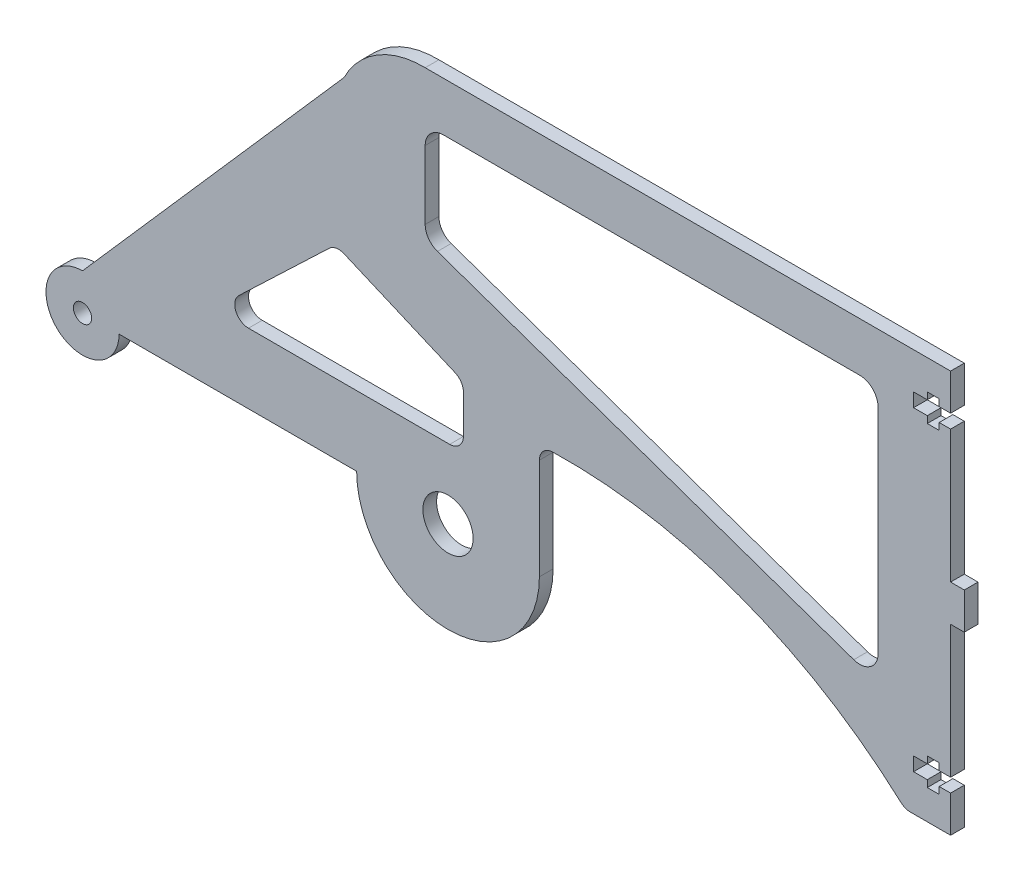
SolidWorks part; units mm, degrees
ref_plane "前视基准面" through (0, 0, 0) normal (0, 0, 1) x (1, 0, 0)
ref_plane "上视基准面" through (0, 0, 0) normal (0, 1, 0) x (1, 0, 0)
ref_plane "右视基准面" through (0, 0, 0) normal (1, 0, 0) x (0, 0, -1)
sketch "草图1" plane through (0, 0, 0) normal (0, 0, 1) x (1, 0, 0)
  line L308 (254.0026, 13.7079) -> (254.0026, 53.7079) construction
  line L334 (234.0026, 13.7079) -> (182.0026, 13.7079)
  line L346 (364.0026, 97.7079) -> (354.0026, 97.7079)
  line L347 (364.0026, 97.7079) -> (364.0026, 89.7079)
  line L348 (361.5026, 89.7079) -> (361.5026, 91.2079)
  line L349 (361.5026, 86.7079) -> (361.5026, 85.2079)
  line L350 (364.0026, 86.7079) -> (361.5026, 86.7079)
  line L351 (361.5026, 91.2079) -> (358.9026, 91.2079)
  line L352 (358.9026, 91.2079) -> (358.9026, 89.7079)
  line L353 (358.9026, 89.7079) -> (355.9026, 89.7079)
  line L354 (355.9026, 86.7079) -> (355.9026, 89.7079)
  line L355 (358.9026, 86.7079) -> (355.9026, 86.7079)
  line L356 (358.9026, 85.2079) -> (358.9026, 86.7079)
  line L357 (361.5026, 85.2079) -> (358.9026, 85.2079)
  line L358 (361.5026, 89.7079) -> (364.0026, 89.7079)
  line L359 (364.0026, 9.7079) -> (364.0026, 17.7079)
  line L360 (364.0026, 20.7079) -> (364.0026, 86.7079) construction
  line L361 (361.5026, 20.7079) -> (361.5026, 22.2079)
  line L362 (361.5026, 17.7079) -> (361.5026, 16.2079)
  line L363 (364.0026, 17.7079) -> (361.5026, 17.7079)
  line L364 (361.5026, 22.2079) -> (358.9026, 22.2079)
  line L365 (358.9026, 22.2079) -> (358.9026, 20.7079)
  line L366 (358.9026, 20.7079) -> (355.9026, 20.7079)
  line L367 (355.9026, 17.7079) -> (355.9026, 20.7079)
  line L368 (358.9026, 17.7079) -> (355.9026, 17.7079)
  line L369 (358.9026, 16.2079) -> (358.9026, 17.7079)
  line L370 (361.5026, 16.2079) -> (358.9026, 16.2079)
  line L371 (361.5026, 20.7079) -> (364.0026, 20.7079)
  line L372 (364.0026, 9.7079) -> (355.1684, 9.7079)
  line L373 (364.0026, 53.7079) -> (254.0026, 53.7079) construction
  line L374 (254.0026, 53.7079) -> (254.0026, 13.7079) construction
  line L375 (274.0026, 13.7079) -> (274.0026, 35.8191)
  line L376 (354.0026, 97.7079) -> (249.0026, 97.7079)
  line L378 (364.0026, 57.7079) -> (364.0026, 86.7079)
  line L379 (364.0026, 57.7079) -> (367.0026, 57.7079)
  line L380 (367.0026, 57.7079) -> (367.0026, 49.7079)
  line L381 (367.0026, 49.7079) -> (364.0026, 49.7079)
  line L382 (364.0026, 49.7079) -> (364.0026, 20.7079)
  line L383 (253.0026, 86.967) -> (344.1293, 86.967)
  line L384 (348.1293, 82.967) -> (348.1293, 36.1724)
  line L385 (342.8102, 32.3961) -> (251.6836, 64.2263)
  line L386 (249.0026, 68.0025) -> (249.0026, 82.967)
  line L388 (255.5496, 43.1726) -> (249.0026, 45.9704)
  line L389 (249.0026, 45.9704) -> (231.2423, 53.5602)
  line L390 (227.9938, 52.9734) -> (208.2594, 34.1674)
  line L391 (210.329, 28.9956) -> (254.3707, 28.9956)
  line L392 (257.3707, 31.9956) -> (257.3707, 40.4139)
  line L393 (174.0026, 21.7079) -> (231.2423, 86.967)
  circle A37 centre (174.0026, 13.7079) radius 2
  circle A38 centre (254.0026, 13.7079) radius 5.5
  circle A40 centre (174.0026, 13.7079) radius 8 construction
  circle A43 centre (254.0026, 13.7079) radius 20 construction
  arc A44 (274.0026, 13.7079) -> (234.0026, 13.7079) centre (254.0026, 13.7079) cw
  arc A45 (353.1542, 10.4846) -> (276.9296, 38.8182) centre (279.5943, -70.7116) ccw
  arc A46 (276.9296, 38.8182) -> (274.0026, 35.8191) centre (277.0026, 35.8191) ccw
  arc A47 (355.1684, 9.7079) -> (353.1542, 10.4846) centre (355.1684, 12.7079) cw
  arc A49 (251.6836, 64.2263) -> (249.0026, 68.0025) centre (253.0026, 68.0025) cw
  arc A50 (249.0026, 82.967) -> (253.0026, 86.967) centre (253.0026, 82.967) cw
  arc A51 (344.1293, 86.967) -> (348.1293, 82.967) centre (344.1293, 82.967) cw
  arc A52 (342.8102, 32.3961) -> (348.1293, 36.1724) centre (344.1293, 36.1724) ccw
  arc A53 (182.0026, 13.7079) -> (174.0026, 21.7079) centre (174.0026, 13.7079) cw
  arc A54 (257.3707, 31.9956) -> (254.3707, 28.9956) centre (254.3707, 31.9956) cw
  arc A55 (210.329, 28.9956) -> (208.2594, 34.1674) centre (210.329, 31.9956) cw
  arc A56 (227.9938, 52.9734) -> (231.2423, 53.5602) centre (230.0634, 50.8016) cw
  arc A57 (257.3707, 40.4139) -> (255.5496, 43.1726) centre (254.3707, 40.4139) ccw
  arc A58 (249.0026, 97.7079) -> (231.2423, 86.967) centre (248.6086, 78.3054) ccw
  dimension "D1" = 3
  dimension "D3" = 3
  dimension "D4" = 4
  dimension "D2" = 3
extrude "凸台-拉伸1" add sketch "草图1" along normal blind 3
sketch "草图2" plane through (364.0026, 0, 0) normal (1, 0, 0) x (0, 0, -1)
  line L0 (-1.5, 20.7079) -> (-1.5, 17.7079)
  line L1 (-3, 20.7079) -> (0, 20.7079) construction
  line L2 (-3, 17.7079) -> (0, 17.7079) construction
  line L3 (-1.5, 89.7079) -> (-1.5, 86.7079)
  line L4 (-3, 89.7079) -> (0, 89.7079) construction
  line L5 (-3, 86.7079) -> (0, 86.7079) construction
  circle A0 centre (-1.5, 19.2079) radius 1.5
  circle A1 centre (-1.5, 88.2079) radius 1.5
